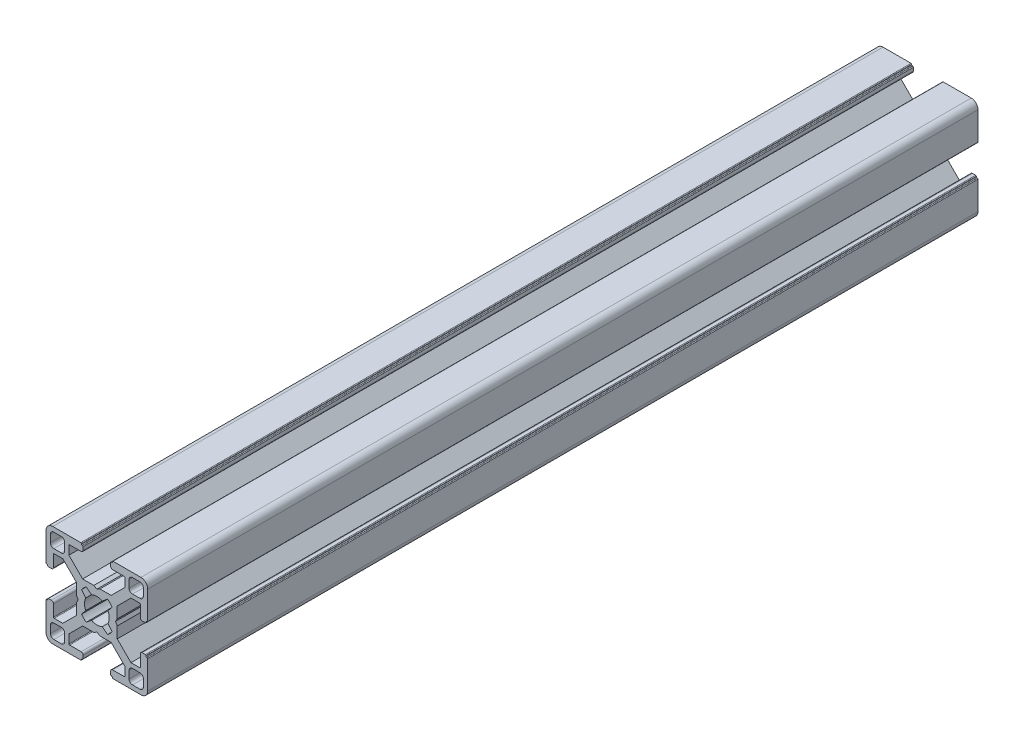
SolidWorks part; units mm, degrees
material "6061 Alloy"
ref_plane "Front" through (0, 0, 0) normal (0, 0, 1) x (1, 0, 0)
ref_plane "Top" through (0, 0, 0) normal (0, 1, 0) x (1, 0, 0)
ref_plane "Right" through (0, 0, 0) normal (1, 0, 0) x (0, 0, -1)
sketch "Sketch1" plane through (0, 0, 0) normal (0, 0, 1) x (1, 0, 0)
  line L0 (13.7, 12.7) -> (13.7, 10.5)
  line L1 (10.5, 9.5) -> (12.7, 9.5)
  line L2 (9.5, 12.7) -> (9.5, 10.5)
  line L3 (10.5, 13.7) -> (12.7, 13.7)
  line L4 (3.1359, 4.5184) -> (1.6001, 3.2806)
  line L5 (3.2806, 1.6001) -> (4.5053, 3.1547)
  line L6 (6.0045, 0.9) -> (5.4849, 0)
  line L7 (6.0045, 4.2045) -> (6.0045, 0.9)
  line L8 (0, -5.4849) -> (0.9, -6)
  line L9 (0.9, -6) -> (4.2045, -6)
  line L10 (4.2045, -6) -> (8.25, -10.05)
  line L11 (8.25, -10.05) -> (8.25, -12.6)
  line L12 (4.65, -12.8) -> (8.05, -12.8)
  line L13 (4.05, -14.3) -> (4.05, -13.4)
  line L14 (4.25, -14.5) -> (4.35, -14.5)
  line L15 (4.55, -14.8) -> (4.55, -14.7)
  line L16 (4.75, -15) -> (13, -15)
  line L17 (15, -13) -> (15, -4.75)
  line L18 (14.7, -4.55) -> (14.8, -4.55)
  line L19 (14.5, -4.35) -> (14.5, -4.25)
  line L20 (13.4, -4.05) -> (14.3, -4.05)
  line L21 (12.8, -8.05) -> (12.8, -4.65)
  line L22 (12.6, -8.25) -> (10.05, -8.25)
  line L23 (10.05, -8.25) -> (6.0045, -4.2045)
  line L24 (6.0045, -4.2045) -> (6.0045, -0.9)
  line L25 (6.0045, -0.9) -> (5.4849, 0)
  line L26 (10.05, 8.25) -> (6.0045, 4.2045)
  line L27 (12.6, 8.25) -> (10.05, 8.25)
  line L28 (12.8, 8.05) -> (12.8, 4.65)
  line L29 (13.4, 4.05) -> (14.3, 4.05)
  line L30 (14.5, 4.35) -> (14.5, 4.25)
  line L31 (14.7, 4.55) -> (14.8, 4.55)
  line L32 (15, 13) -> (15, 4.75)
  line L33 (4.75, 15) -> (13, 15)
  line L34 (4.55, 14.8) -> (4.55, 14.7)
  line L35 (4.25, 14.5) -> (4.35, 14.5)
  line L36 (4.05, 14.3) -> (4.05, 13.4)
  line L37 (4.65, 12.8) -> (8.05, 12.8)
  line L38 (8.25, 10.05) -> (8.25, 12.6)
  line L39 (4.2045, 6) -> (8.25, 10.05)
  line L40 (0.9, 6) -> (4.2045, 6)
  line L41 (0, 5.4849) -> (0.9, 6)
  line L42 (-13.7, -12.7) -> (-13.7, -10.5)
  line L43 (-10.5, -9.5) -> (-12.7, -9.5)
  line L44 (-9.5, -12.7) -> (-9.5, -10.5)
  line L45 (-10.5, -13.7) -> (-12.7, -13.7)
  line L46 (-3.1359, -4.5184) -> (-1.6001, -3.2806)
  line L47 (-3.2806, -1.6001) -> (-4.5053, -3.1547)
  line L48 (0, 5.4849) -> (-0.9, 6)
  line L49 (-0.9, 6) -> (-4.2045, 6)
  line L50 (-4.2045, 6) -> (-8.25, 10.05)
  line L51 (-8.25, 10.05) -> (-8.25, 12.6)
  line L52 (-4.65, 12.8) -> (-8.05, 12.8)
  line L53 (-4.05, 14.3) -> (-4.05, 13.4)
  line L54 (-4.25, 14.5) -> (-4.35, 14.5)
  line L55 (-4.55, 14.8) -> (-4.55, 14.7)
  line L56 (-4.75, 15) -> (-13, 15)
  line L57 (-15, 13) -> (-15, 4.75)
  line L58 (-14.7, 4.55) -> (-14.8, 4.55)
  line L59 (-14.5, 4.35) -> (-14.5, 4.25)
  line L60 (-13.4, 4.05) -> (-14.3, 4.05)
  line L61 (-12.8, 8.05) -> (-12.8, 4.65)
  line L62 (-12.6, 8.25) -> (-10.05, 8.25)
  line L63 (-10.05, 8.25) -> (-6.0045, 4.2045)
  line L64 (-6.0045, -0.9) -> (-5.4849, 0)
  line L65 (-6.0045, -4.2045) -> (-6.0045, -0.9)
  line L66 (-10.05, -8.25) -> (-6.0045, -4.2045)
  line L67 (-12.6, -8.25) -> (-10.05, -8.25)
  line L68 (-12.8, -8.05) -> (-12.8, -4.65)
  line L69 (-13.4, -4.05) -> (-14.3, -4.05)
  line L70 (-14.5, -4.35) -> (-14.5, -4.25)
  line L71 (-14.7, -4.55) -> (-14.8, -4.55)
  line L72 (-15, -13) -> (-15, -4.75)
  line L73 (-4.75, -15) -> (-13, -15)
  line L74 (-4.55, -14.8) -> (-4.55, -14.7)
  line L75 (-4.25, -14.5) -> (-4.35, -14.5)
  line L76 (-4.05, -14.3) -> (-4.05, -13.4)
  line L77 (3.2806, -1.6001) -> (4.5053, -3.1547)
  line L78 (3.1359, -4.5184) -> (1.6001, -3.2806)
  line L79 (-4.65, -12.8) -> (-8.05, -12.8)
  line L80 (-8.25, -10.05) -> (-8.25, -12.6)
  line L81 (-4.2045, -6) -> (-8.25, -10.05)
  line L82 (-0.9, -6) -> (-4.2045, -6)
  line L83 (0, -5.4849) -> (-0.9, -6)
  line L84 (10.5, -13.7) -> (12.7, -13.7)
  line L85 (9.5, -12.7) -> (9.5, -10.5)
  line L86 (10.5, -9.5) -> (12.7, -9.5)
  line L87 (13.7, -12.7) -> (13.7, -10.5)
  line L88 (-6.0045, 4.2045) -> (-6.0045, 0.9)
  line L89 (-6.0045, 0.9) -> (-5.4849, 0)
  line L90 (-3.2806, 1.6001) -> (-4.5053, 3.1547)
  line L91 (-3.1359, 4.5184) -> (-1.6001, 3.2806)
  line L92 (-10.5, 13.7) -> (-12.7, 13.7)
  line L93 (-9.5, 12.7) -> (-9.5, 10.5)
  line L94 (-10.5, 9.5) -> (-12.7, 9.5)
  line L95 (-13.7, 12.7) -> (-13.7, 10.5)
  line L96 (-23.4857, 0) -> (20.9308, 0) construction
  line L97 (0, 17.9563) -> (0, -17.361) construction
  arc A0 (13.7, 12.7) -> (12.7, 13.7) centre (12.7, 12.7) ccw
  arc A1 (12.7, 9.5) -> (13.7, 10.5) centre (12.7, 10.5) ccw
  arc A2 (9.5, 10.5) -> (10.5, 9.5) centre (10.5, 10.5) ccw
  arc A3 (10.5, 13.7) -> (9.5, 12.7) centre (10.5, 12.7) ccw
  arc A4 (1.6001, 3.2806) -> (-1.6001, 3.2806) centre (0, 0) ccw
  arc A5 (8.25, -12.6) -> (8.05, -12.8) centre (8.05, -12.6) cw
  arc A6 (4.65, -12.8) -> (4.05, -13.4) centre (4.65, -13.4) ccw
  arc A7 (4.05, -14.3) -> (4.25, -14.5) centre (4.25, -14.3) ccw
  arc A8 (4.35, -14.5) -> (4.55, -14.7) centre (4.35, -14.7) cw
  arc A9 (4.55, -14.8) -> (4.75, -15) centre (4.75, -14.8) ccw
  arc A10 (13, -15) -> (15, -13) centre (13, -13) ccw
  arc A11 (15, -4.75) -> (14.8, -4.55) centre (14.8, -4.75) ccw
  arc A12 (14.7, -4.55) -> (14.5, -4.35) centre (14.7, -4.35) cw
  arc A13 (14.5, -4.25) -> (14.3, -4.05) centre (14.3, -4.25) ccw
  arc A14 (13.4, -4.05) -> (12.8, -4.65) centre (13.4, -4.65) ccw
  arc A15 (12.8, -8.05) -> (12.6, -8.25) centre (12.6, -8.05) cw
  arc A16 (4.5053, 3.1547) -> (3.1359, 4.5184) centre (0, 0) ccw
  arc A17 (12.8, 8.05) -> (12.6, 8.25) centre (12.6, 8.05) ccw
  arc A18 (13.4, 4.05) -> (12.8, 4.65) centre (13.4, 4.65) cw
  arc A19 (14.5, 4.25) -> (14.3, 4.05) centre (14.3, 4.25) cw
  arc A20 (14.7, 4.55) -> (14.5, 4.35) centre (14.7, 4.35) ccw
  arc A21 (15, 4.75) -> (14.8, 4.55) centre (14.8, 4.75) cw
  arc A22 (13, 15) -> (15, 13) centre (13, 13) cw
  arc A23 (4.55, 14.8) -> (4.75, 15) centre (4.75, 14.8) cw
  arc A24 (4.35, 14.5) -> (4.55, 14.7) centre (4.35, 14.7) ccw
  arc A25 (4.05, 14.3) -> (4.25, 14.5) centre (4.25, 14.3) cw
  arc A26 (4.65, 12.8) -> (4.05, 13.4) centre (4.65, 13.4) cw
  arc A27 (8.25, 12.6) -> (8.05, 12.8) centre (8.05, 12.6) ccw
  arc A28 (-13.7, -12.7) -> (-12.7, -13.7) centre (-12.7, -12.7) ccw
  arc A29 (-12.7, -9.5) -> (-13.7, -10.5) centre (-12.7, -10.5) ccw
  arc A30 (-9.5, -10.5) -> (-10.5, -9.5) centre (-10.5, -10.5) ccw
  arc A31 (-10.5, -13.7) -> (-9.5, -12.7) centre (-10.5, -12.7) ccw
  arc A32 (-4.5053, -3.1547) -> (-3.1359, -4.5184) centre (0, 0) ccw
  arc A33 (-3.2806, 1.6001) -> (-3.2806, -1.6001) centre (0, 0) ccw
  arc A34 (-8.25, 12.6) -> (-8.05, 12.8) centre (-8.05, 12.6) cw
  arc A35 (-4.65, 12.8) -> (-4.05, 13.4) centre (-4.65, 13.4) ccw
  arc A36 (-4.05, 14.3) -> (-4.25, 14.5) centre (-4.25, 14.3) ccw
  arc A37 (-4.35, 14.5) -> (-4.55, 14.7) centre (-4.35, 14.7) cw
  arc A38 (-4.55, 14.8) -> (-4.75, 15) centre (-4.75, 14.8) ccw
  arc A39 (-13, 15) -> (-15, 13) centre (-13, 13) ccw
  arc A40 (-15, 4.75) -> (-14.8, 4.55) centre (-14.8, 4.75) ccw
  arc A41 (-14.7, 4.55) -> (-14.5, 4.35) centre (-14.7, 4.35) cw
  arc A42 (-14.5, 4.25) -> (-14.3, 4.05) centre (-14.3, 4.25) ccw
  arc A43 (-13.4, 4.05) -> (-12.8, 4.65) centre (-13.4, 4.65) ccw
  arc A44 (-12.8, 8.05) -> (-12.6, 8.25) centre (-12.6, 8.05) cw
  arc A45 (-4.5053, 3.1547) -> (-3.1359, 4.5184) centre (0, 0) cw
  arc A46 (-12.8, -8.05) -> (-12.6, -8.25) centre (-12.6, -8.05) ccw
  arc A47 (-13.4, -4.05) -> (-12.8, -4.65) centre (-13.4, -4.65) cw
  arc A48 (-14.5, -4.25) -> (-14.3, -4.05) centre (-14.3, -4.25) cw
  arc A49 (3.2806, 1.6001) -> (3.2806, -1.6001) centre (0, 0) cw
  arc A50 (4.5053, -3.1547) -> (3.1359, -4.5184) centre (0, 0) cw
  arc A51 (1.6001, -3.2806) -> (-1.6001, -3.2806) centre (0, 0) cw
  arc A52 (-14.7, -4.55) -> (-14.5, -4.35) centre (-14.7, -4.35) ccw
  arc A53 (-15, -4.75) -> (-14.8, -4.55) centre (-14.8, -4.75) cw
  arc A54 (-13, -15) -> (-15, -13) centre (-13, -13) cw
  arc A55 (-4.55, -14.8) -> (-4.75, -15) centre (-4.75, -14.8) cw
  arc A56 (10.5, -13.7) -> (9.5, -12.7) centre (10.5, -12.7) cw
  arc A57 (9.5, -10.5) -> (10.5, -9.5) centre (10.5, -10.5) cw
  arc A58 (12.7, -9.5) -> (13.7, -10.5) centre (12.7, -10.5) cw
  arc A59 (13.7, -12.7) -> (12.7, -13.7) centre (12.7, -12.7) cw
  arc A60 (-4.35, -14.5) -> (-4.55, -14.7) centre (-4.35, -14.7) ccw
  arc A61 (-4.05, -14.3) -> (-4.25, -14.5) centre (-4.25, -14.3) cw
  arc A62 (-4.65, -12.8) -> (-4.05, -13.4) centre (-4.65, -13.4) cw
  arc A63 (-8.25, -12.6) -> (-8.05, -12.8) centre (-8.05, -12.6) ccw
  arc A64 (-10.5, 13.7) -> (-9.5, 12.7) centre (-10.5, 12.7) cw
  arc A65 (-9.5, 10.5) -> (-10.5, 9.5) centre (-10.5, 10.5) cw
  arc A66 (-12.7, 9.5) -> (-13.7, 10.5) centre (-12.7, 10.5) cw
  arc A67 (-13.7, 12.7) -> (-12.7, 13.7) centre (-12.7, 12.7) cw
  point P81 (15, 15)
  point P82 (0, 15)
  point P203 (0, -15)
  point P204 (15, -15)
  point P206 (0, 0)
  point P207 (15, 0)
  point P219 (-15, 0)
  point P220 (-15, -15)
  point P221 (-15, 15)
  dimension "D6" = 7.3
  dimension "D7" = 11
  dimension "D1" = 30
  dimension "D2" = 15
  dimension "D3" = 30
  dimension "D4" = 8.1
  dimension "D5" = 9
  dimension "D8" = 8.1
extrude "Boss-Extrude1" add sketch "Sketch1" along normal blind 244.8
